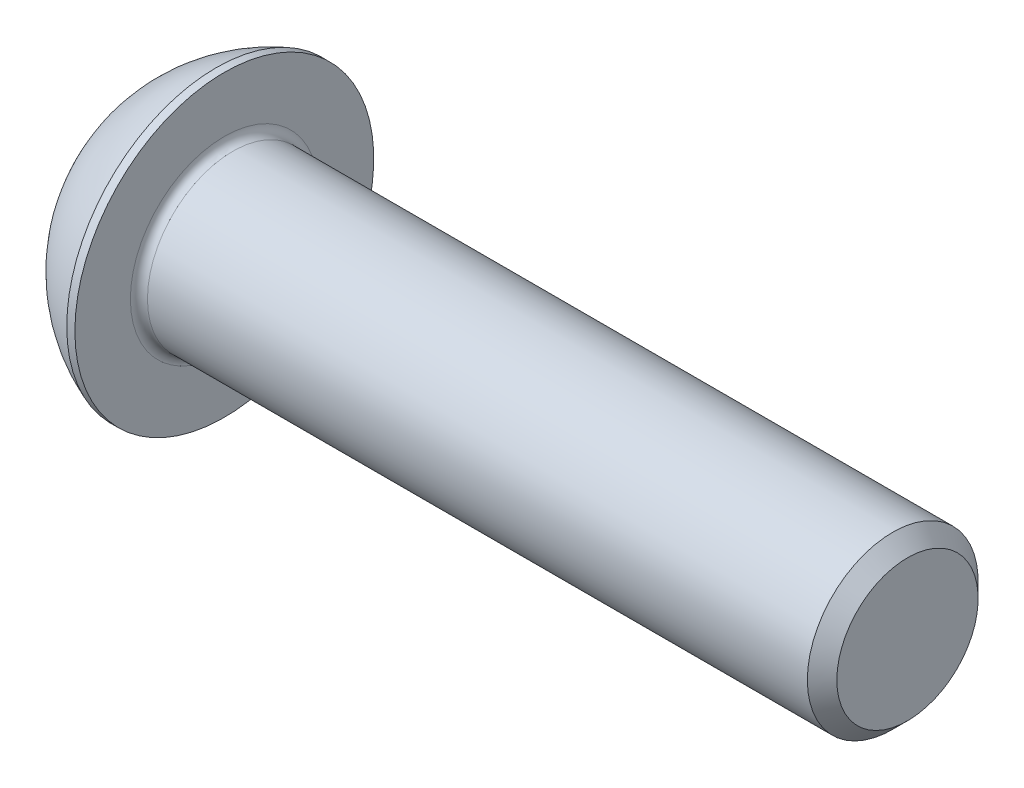
SolidWorks part; units mm, degrees
material "Plain Carbon Steel"
ref_plane "Plane1" through (0, 0, 0) normal (0, 0, 1) x (1, 0, 0)
ref_plane "Plane2" through (0, 0, 0) normal (0, 1, 0) x (1, 0, 0)
ref_plane "Plane3" through (0, 0, 0) normal (1, 0, 0) x (0, 0, -1)
sketch "BodySke" plane through (0, 0, 0) normal (0, 0, 1) x (1, 0, 0)
  line L0 (36.4, 0) -> (36.4, 3.3095)
  line L1 (35.7095, 4) -> (4.4, 4)
  line L2 (4.4, 4) -> (4.4, 7)
  line L3 (4.4, 7) -> (4.02, 7)
  line L4 (0, 0) -> (101.6, 0) construction
  line L5 (4.4, -7) -> (4.02, -7) construction
  line L6 (55.6768, -4) -> (4.4, -4) construction
  line L7 (36.4, 0) -> (0, 0)
  line L8 (0, 3.5) -> (0, -3.5) construction
  line L9 (0, 0) -> (0, 3.5)
  line L10 (36.4, 3.3095) -> (35.7095, 4)
  line L11 (36.4, -3.3095) -> (35.7095, -4) construction
  line L12 (5.65, 9.525) -> (5.65, -4) construction
  line L13 (4.4, 9.525) -> (4.4, -4) construction
  arc A1 (0, 3.5) -> (4.02, 7) centre (6.5809, 0) cw
  dimension "Diameter" = 8
  dimension "Length" = 32
  dimension "Head_dia" = 14
  dimension "D1" = 7
  dimension "Head_ht" = 4.4
  dimension "Head_side_ht" = 0.38
  dimension "Minor_dia" = 6.619
  dimension "Body_ch_ang" = 45
  dimension "Advance" = 1.25
  dimension "Thread_nom" = 32
revolve "BaseBody" add sketch "BodySke" angle 360 about L4
cosmetic thread "ThreadCosmetic" parameters "Thread_length"=29.5, "Thread_minor"=6.619
fillet "Fillet1" radius 0.4 1 edges at (4.4, 0, 4)
sketch "Sketch2" plane through (0, 0, 0) normal (0, 0, 1) x (1, 0, 0)
  line L0 (0, 2.5) -> (2.6, 2.5)
  line L1 (2.6, 2.5) -> (4.0434, 0)
  line L3 (4.0434, 0) -> (0, 0)
  line L4 (0, 0) -> (0, 2.5)
  line L5 (0, -2.5) -> (2.6, -2.5) construction
  line L6 (0, 0) -> (47.625, 0) construction
  dimension "D2" = 60
  dimension "PreBroach_depth" = 2.6
  dimension "PreBroach_dia" = 5
revolve "PreBroach" cut sketch "Sketch2" angle 360 about L6
sketch "Sketch3" plane through (0, 0, 0) normal (1, 0, 0) x (0, 0, -1)
  line L0 (-2.5, -1.4434) -> (-2.5, 1.4434)
  line L1 (-2.5, 1.4434) -> (0, 2.8868)
  line L2 (0, 2.8868) -> (2.5, 1.4434)
  line L3 (2.5, 1.4434) -> (2.5, -1.4434)
  line L4 (2.5, -1.4434) -> (0, -2.8868)
  line L5 (0, -2.8868) -> (-2.5, -1.4434)
  dimension "Hex_size" = 5
  dimension "D3" = 5
  dimension "D1" = 2.5
  dimension "D2" = 2.5
extrude "Hex" cut sketch "Sketch3" along normal blind 2.6
sketch "ThdSchSke" plane through (0, 0, 0) normal (0, 0, 1) x (1, 0, 0)
  line L0 (6.9, -3.3095) -> (6.4165, -4)
  line L1 (6.9, -3.3095) -> (7.3835, -4)
  line L2 (7.3835, -4) -> (7.3835, -5)
  line L3 (-3.175, 0) -> (5.1513, 0) construction
  line L5 (7.3835, -5) -> (6.4165, -5)
  line L6 (6.4165, -5) -> (6.4165, -4)
  dimension "Diameter" = 8
  dimension "Thread_minor" = 6.619
  dimension "SideAngle" = 55
  dimension "VeeAngle" = 70
  dimension "Overcut" = 10
  dimension "Start" = 6.9
revolve "ThreadSchematic" [suppressed] cut sketch "ThdSchSke" angle 360 about L3
pattern_linear "ThdSchPat" [suppressed]
equation "\"D1@BodySke\" = \"Head_dia@BodySke\" * .5"
equation "\"Thread_minor@ThreadCosmetic\" = \"Minor_dia@BodySke\""
equation "\"D1@Sketch3\" = \"Hex_size@Sketch3\" / 2"
equation "\"D2@Sketch3\" = \"D1@Sketch3\""
equation "\"D3@Sketch3\" = \"Hex_size@Sketch3\""
equation "\"Thread_length@ThreadCosmetic\" = ((sgn( (\"Length@BodySke\" - \"Advance@BodySke\" * 2.0) - \"Thread_nom@BodySke\" )-1)*( (\"Length@BodySke\" - \"Advance@BodySke\" * 2.0) - \"Thread_nom@BodySke\" ))/-2+ \"Thread_nom@BodySke\""
equation "\"Thread_minor@ThdSchSke\" = \"Minor_dia@BodySke\""
equation "\"Diameter@ThdSchSke\" = \"Diameter@BodySke\""
equation "\"Overcut@ThdSchSke\" = \"Diameter@BodySke\" * 1.25"
equation "\"Start@ThdSchSke\" = \"Head_ht@BodySke\" + \"Length@BodySke\" - \"Thread_length@ThreadCosmetic\"  '---Non-countersunk---"
equation "\"Num_threads@ThdSchPat\" = int( \"Thread_length@ThreadCosmetic\" / \"Advance@BodySke\" + 0.999 )  + 1"
equation "\"Advance@ThdSchPat\" = \"Thread_length@ThreadCosmetic\" /  (\"Num_threads@ThdSchPat\" - 1) 'relax it"
equation "\"Num_threads@ThdSchPat\" = \"Num_threads@ThdSchPat\" - sgn( \"Num_threads@ThdSchPat\" - 1) '---chamfered tips only---"
